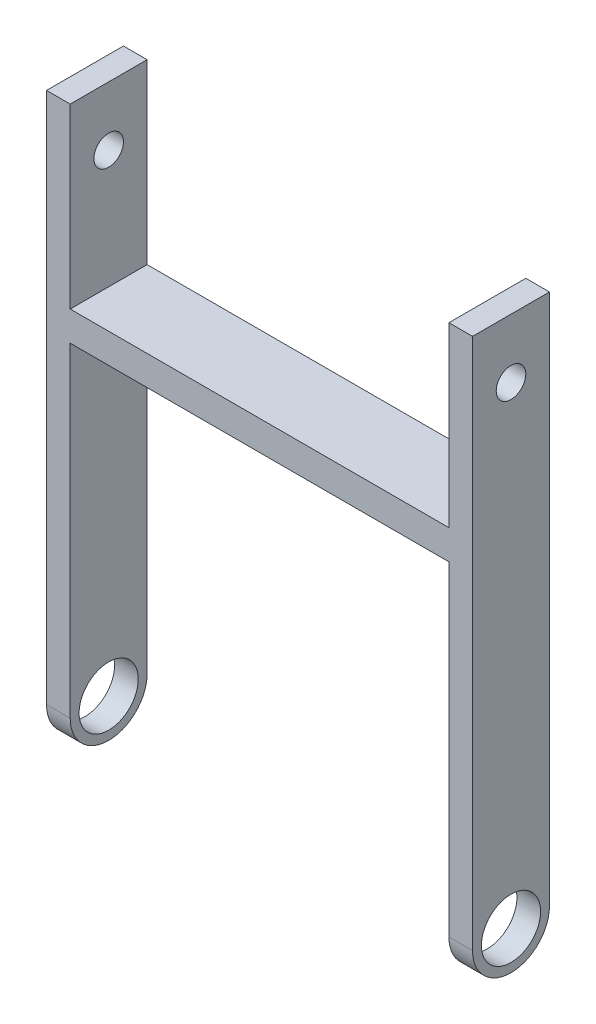
SolidWorks part; units mm, degrees
ref_plane "Plan de face" through (0, 0, 0) normal (0, 0, 1) x (1, 0, 0)
ref_plane "Plan de dessus" through (0, 0, 0) normal (0, 1, 0) x (1, 0, 0)
ref_plane "Plan de droite" through (0, 0, 0) normal (1, 0, 0) x (0, 0, -1)
sketch "Esquisse1" plane through (0, 0, 0) normal (0, 0, 1) x (1, 0, 0)
  line L0 (0, 0) -> (0, 100)
  line L1 (0, 100) -> (4, 100)
  line L2 (4, 100) -> (4, 70)
  line L3 (4, 70) -> (68, 70)
  line L4 (68, 70) -> (68, 100)
  line L5 (68, 100) -> (72, 100)
  line L6 (72, 100) -> (72, 0)
  line L7 (72, 0) -> (68, 0)
  line L8 (68, 0) -> (68, 65)
  line L9 (68, 65) -> (4, 65)
  line L10 (4, 65) -> (4, 0)
  line L11 (4, 0) -> (0, 0)
  dimension "D1" = 4
  dimension "D2" = 4
  dimension "D3" = 100
  dimension "D4" = 100
  dimension "D5" = 5
  dimension "D6" = 30
  dimension "D7" = 64
  dimension "D8" = 72
extrude "Boss.-Extru.1" add sketch "Esquisse1" along normal blind 13
sketch "Esquisse2" plane through (72, 0, 0) normal (1, 0, 0) x (0, 0, -1)
  line L0 (-13, 10.1) -> (0, 10.1) construction
  line L1 (-13, 0) -> (-13, 100) construction
  line L2 (0, 0) -> (0, 100) construction
  line L3 (0, 10.1) -> (-6.5, 0) construction
  line L4 (-13, 0) -> (0, 0) construction
  line L5 (-6.5, 0) -> (-6.5, 111.6531) construction
  circle A0 centre (-6.5, 10.1) radius 5
  dimension "D2" = 10
  dimension "D1" = 10.1
extrude "Enlèv. mat.-Extru.1" cut sketch "Esquisse2" against normal through all
sketch "Esquisse3" plane through (0, 0, 0) normal (-1, 0, 0) x (0, 0, 1)
  line L0 (0, 90) -> (13, 90) construction
  line L1 (0, 100) -> (0, 0) construction
  line L2 (13, 100) -> (13, 0) construction
  line L3 (13, 90) -> (6.5, 100) construction
  line L4 (13, 100) -> (0, 100) construction
  line L5 (6.5, 100) -> (6.5, -7.8895) construction
  circle A0 centre (6.5, 90) radius 2.5
  dimension "D2" = 5
  dimension "D1" = 10
extrude "Enlèv. mat.-Extru.2" cut sketch "Esquisse3" against normal through all
sketch "Esquisse5" plane through (0, 0, 0) normal (-1, 0, 0) x (0, 0, 1)
  line L6 (0, 100) -> (0, 0) construction
  line L7 (13, 100) -> (13, 0) construction
  line L8 (0, 10.1) -> (0, -2.9809)
  line L9 (0, -2.9809) -> (15.0015, -2.9809)
  line L10 (15.0015, -2.9809) -> (15.0015, 10.1)
  line L11 (15.0015, 10.1) -> (13, 10.1)
  arc A0 (0, 10.1) -> (13, 10.1) centre (6.5, 10.1) ccw
  dimension "D1" = 15.0015
  dimension "D2" = 13.0809
  dimension "D3" = 13.0809
extrude "Enlèv. mat.-Extru.4" cut sketch "Esquisse5" against normal through all
